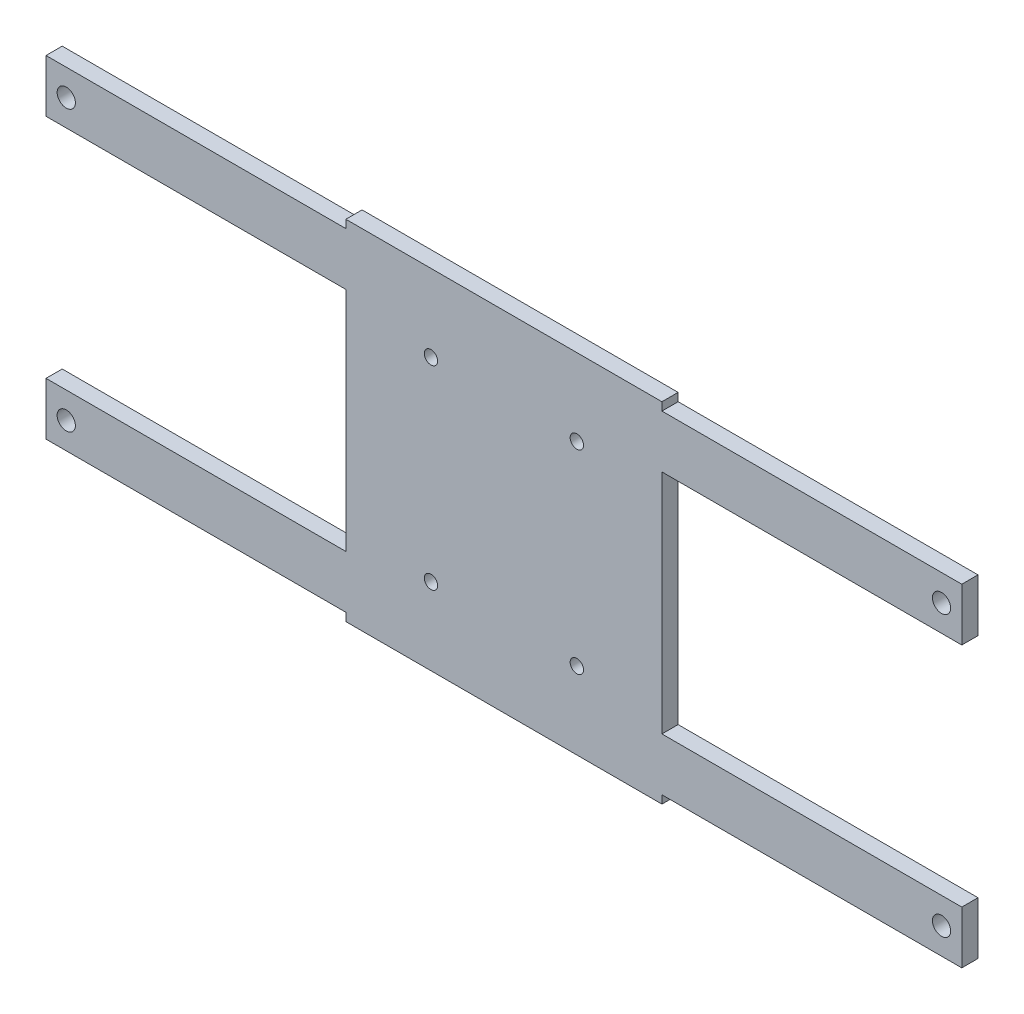
SolidWorks part; units mm, degrees
ref_plane "前视基准面" through (0, 0, 0) normal (0, 0, 1) x (1, 0, 0)
ref_plane "上视基准面" through (0, 0, 0) normal (0, 1, 0) x (1, 0, 0)
ref_plane "右视基准面" through (0, 0, 0) normal (1, 0, 0) x (0, 0, -1)
other "Configuration Table"
sketch "Sketch_Sensor_bridge" plane through (0, 0, 0) normal (0, 0, 1) x (1, 0, 0)
  line L0 (113, -28) -> (113, -41)
  line L1 (113, -41) -> (39, -41)
  line L2 (39, -41) -> (39, -43)
  line L3 (39, -43) -> (-39, -43)
  line L4 (-39, -43) -> (-39, -41)
  line L5 (-39, -41) -> (-113, -41)
  line L6 (-113, -41) -> (-113, -28)
  line L7 (-113, -28) -> (-39, -28)
  line L8 (-39, -28) -> (-39, 28)
  line L9 (-39, 28) -> (-113, 28)
  line L10 (-113, 28) -> (-113, 41)
  line L11 (-113, 41) -> (-39, 41)
  line L12 (-39, 41) -> (-39, 43)
  line L13 (-39, 43) -> (39, 43)
  line L14 (39, 43) -> (39, 41)
  line L15 (39, 41) -> (113, 41)
  line L16 (113, 41) -> (113, 28)
  line L17 (113, 28) -> (39, 28)
  line L18 (39, 28) -> (39, -28)
  line L19 (39, -28) -> (113, -28)
extrude "Sensor_bridge" add sketch "Sketch_Sensor_bridge" along normal blind 4 from offset 0
sketch "Sketch_Deck_columns_M4" plane through (0, 0, 0) normal (0, 0, 1) x (1, 0, 0)
  circle A0 centre (-108, -34.5) radius 2.25
  circle A1 centre (-108, 34.5) radius 2.25
  circle A2 centre (108, -34.5) radius 2.25
  circle A3 centre (108, 34.5) radius 2.25
  dimension "D1" = 4.5
  dimension "D4" = 4.5
  dimension "D7" = 4.5
  dimension "D10" = 4.5
  dimension "D2" = 108
  dimension "D3" = 34.5
  dimension "D5" = 108
  dimension "D6" = 34.5
  dimension "D8" = 108
  dimension "D9" = 34.5
  dimension "D11" = 108
  dimension "D12" = 34.5
extrude "Deck_columns_M4" cut sketch "Sketch_Deck_columns_M4" along normal blind 6 from offset 1
sketch "Sketch_MID360_mount" plane through (0, 0, 0) normal (0, 0, 1) x (1, 0, 0)
  circle A0 centre (-18, -24) radius 1.65
  circle A1 centre (-18, 24) radius 1.65
  circle A2 centre (18, -24) radius 1.65
  circle A3 centre (18, 24) radius 1.65
  dimension "D1" = 3.3
  dimension "D4" = 3.3
  dimension "D7" = 3.3
  dimension "D10" = 3.3
  dimension "D2" = 18
  dimension "D3" = 24
  dimension "D5" = 18
  dimension "D6" = 24
  dimension "D8" = 18
  dimension "D9" = 24
  dimension "D11" = 18
  dimension "D12" = 24
extrude "MID360_mount" cut sketch "Sketch_MID360_mount" along normal blind 6 from offset 1
